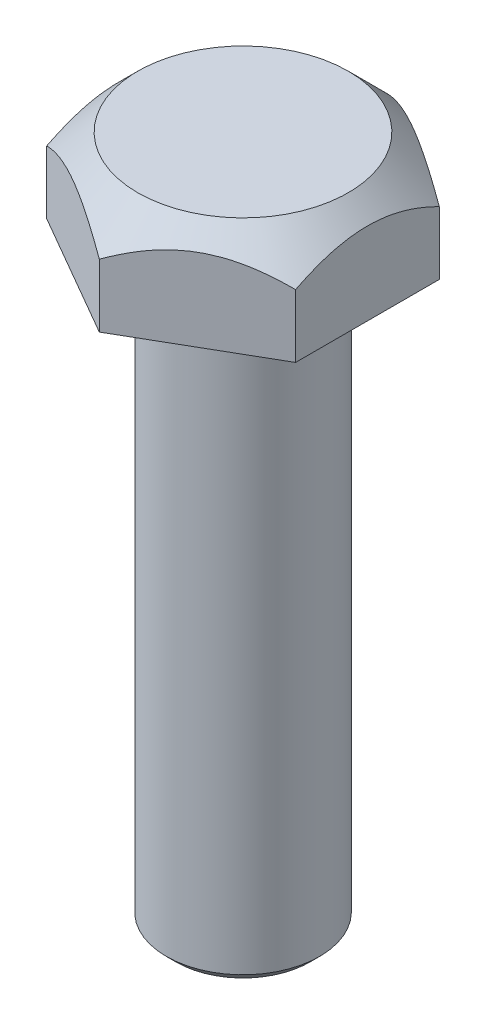
SolidWorks part; units mm, degrees
ref_plane "Front Plane" through (0, 0, 0) normal (0, 0, 1) x (1, 0, 0)
ref_plane "Top Plane" through (0, 0, 0) normal (0, 1, 0) x (1, 0, 0)
ref_plane "Right Plane" through (0, 0, 0) normal (1, 0, 0) x (0, 0, -1)
sketch "Sketch1" plane through (0, 0, 0) normal (0, 1, 0) x (1, 0, 0)
  line L1 (0, 7.5056) -> (-6.5, 3.7528)
  line L2 (-6.5, 3.7528) -> (-6.5, -3.7528)
  line L3 (-6.5, -3.7528) -> (0, -7.5056)
  line L4 (0, -7.5056) -> (6.5, -3.7528)
  line L5 (6.5, -3.7528) -> (6.5, 3.7528)
  line L6 (6.5, 3.7528) -> (0, 7.5056)
  dimension "D1" = 13
extrude "Boss-Extrude1" add sketch "Sketch1" along normal blind 5.3
sketch "Sketch2" plane through (0, 0, 0) normal (0, 1, 0) x (1, 0, 0)
  circle A0 centre (0, 0) radius 4
extrude "Boss-Extrude3" add sketch "Sketch2" against normal blind 30.5
chamfer "Chamfer5" distance 0.5 angle 45 1 edges at (0, -30.5, 4)
sketch "Sketch4" plane through (0, 5.3, 0) normal (0, 1, 0) x (1, 0, 0)
  circle A0 centre (0, 0) radius 5.5
extrude "Cut-Extrude7" cut sketch "Sketch4" against normal blind 2 draft 45 flip side to cut
